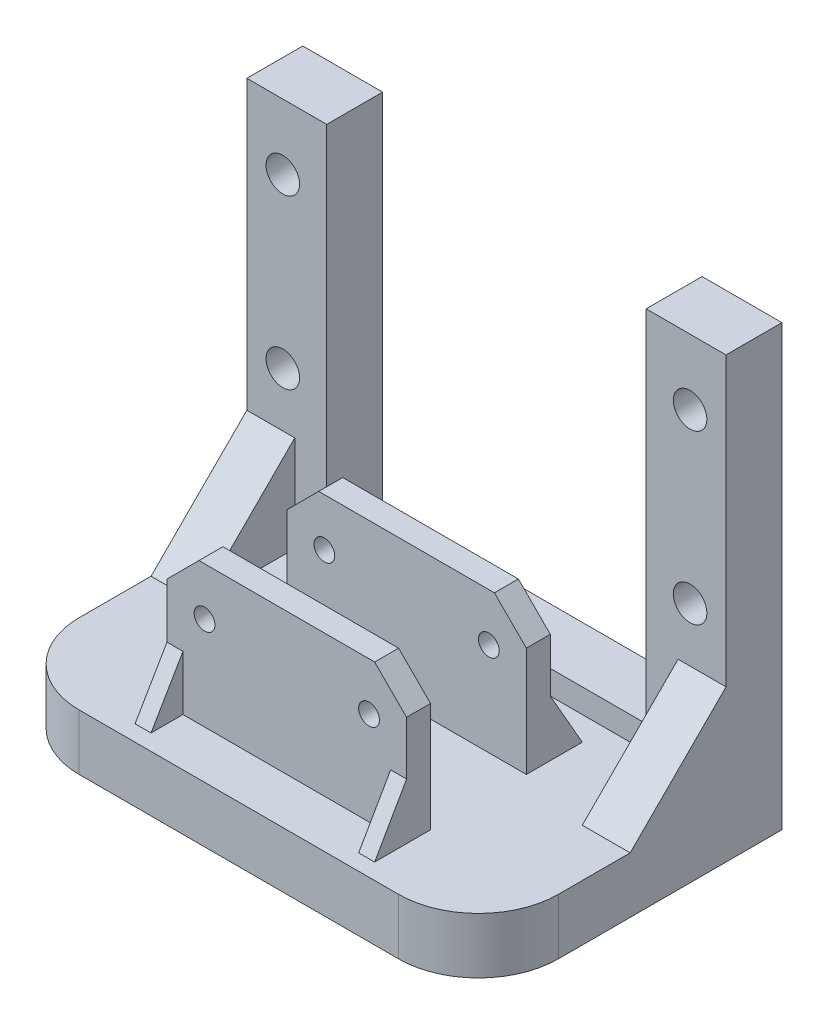
SolidWorks part; units mm, degrees
material "ABS"
ref_plane "前视基准面" through (0, 0, 0) normal (0, 0, 1) x (1, 0, 0)
ref_plane "上视基准面" through (0, 0, 0) normal (0, 1, 0) x (1, 0, 0)
ref_plane "右视基准面" through (0, 0, 0) normal (1, 0, 0) x (0, 0, -1)
other "Configuration Table"
sketch "草图2" plane through (0, 0, 0) normal (0, 0, 1) x (1, 0, 0)
  line L0 (0, 17.5458) -> (0, -16.2036) construction
  line L1 (-11, 11) -> (11, 11)
  line L2 (-15, 7) -> (-15, -11)
  line L3 (-15, -11) -> (15, -11)
  line L5 (-17.0124, 0) -> (19.7175, 0) construction
  line L7 (-15, 7) -> (-11, 11)
  line L8 (15, 7) -> (11, 11)
  line L9 (15, 7) -> (15, -11)
  circle A0 centre (-10.3, 5) radius 1.3
  circle A1 centre (10.3, 5) radius 1.3
  point P0 (0, 0)
  point P4 (0, -11)
  point P15 (0, 11)
  dimension "D4" = 2.6
  dimension "D1" = 18
  dimension "D2" = 15
  dimension "D3" = 16
  dimension "D5" = 11
  dimension "D6" = 22
  dimension "D7" = 10.3
extrude "凸台-拉伸1" add sketch "草图2" along normal mid plane 18
sketch "草图3" plane through (0, 0, 0) normal (0, 0, 1) x (1, 0, 0)
  line L0 (-15, 7) -> (-15, -11) construction
  line L1 (-15, -6.7) -> (15, -6.7)
  line L2 (-15, -6.7) -> (-15, 14.1356)
  line L3 (-15, 14.1356) -> (15, 14.1356)
  line L4 (15, -6.7) -> (15, 14.1356)
  line L5 (15, -11) -> (15, 7) construction
  line L6 (-15, -11) -> (15, -11) construction
  dimension "D1" = 4.3
extrude "切除-拉伸1" cut sketch "草图3" against normal mid plane 12
sketch "草图6" plane through (0, 0, 0) normal (0, 1, 0) x (1, 0, 0)
  line L0 (0, 27.975) -> (0, -21.7187) construction
  line L7 (31, 23) -> (-31, 23) construction
  line L8 (-20, -15) -> (20, -15)
  line L9 (-30, -5) -> (-30, 23)
  line L10 (-30, 23) -> (30, 23)
  line L11 (30, -5) -> (30, 23)
  line L12 (-30, -15) -> (30, 23) construction
  line L13 (-30, 23) -> (30, -15) construction
  arc A4 (-20, -15) -> (-30, -5) centre (-20, -5) cw
  arc A5 (30, -5) -> (20, -15) centre (20, -5) cw
  point P0 (0, 0)
  point P8 (0, 4)
  dimension "D3" = 38
  dimension "D4" = 60
  dimension "D1" = 10
  dimension "D2" = 10
extrude "凸台-拉伸2" add sketch "草图6" against normal blind 7 from surface at -6.7 starting at face at (0, -6.7, 0)
sketch "草图7" plane through (15, 0, 0) normal (1, 0, 0) x (0, 0, -1)
  line L0 (0, 12.9393) -> (0, -16.8041) construction
  line L1 (-9, 0.3) -> (-13, -6.7)
  line L2 (-9, -6.7) -> (-9, 7) construction
  line L4 (-13, -6.7) -> (-9, -6.7)
  line L5 (-9, -6.7) -> (-9, 0.3)
  line L6 (9, -6.7) -> (9, 0.3)
  line L7 (13, -6.7) -> (9, -6.7)
  line L8 (9, 0.3) -> (13, -6.7)
  dimension "D1" = 7
  dimension "D2" = 4
extrude "凸台-拉伸3" add sketch "草图7" against normal blind 2
sketch "草图10" plane through (-15, 0, 0) normal (-1, 0, 0) x (0, 0, 1)
  line L0 (0, 11.4837) -> (0, -16.1999) construction
  line L1 (-9, 0.15) -> (-13, -6.7)
  line L2 (-9, 7) -> (-9, -6.7) construction
  line L3 (-13, -6.7) -> (-9, -6.7)
  line L4 (-9, -6.7) -> (-9, 0.15)
  line L5 (9, -6.7) -> (9, 0.15)
  line L6 (13, -6.7) -> (9, -6.7)
  line L7 (9, 0.15) -> (13, -6.7)
extrude "凸台-拉伸4" add sketch "草图10" against normal blind 2
sketch "草图11" plane through (0, 0, -23) normal (0, 0, 1) x (1, 0, 0)
  line L1 (-30, -11.7) -> (30, -11.7)
  line L2 (-30, -11.7) -> (-30, 41.3)
  line L3 (-30, 41.3) -> (-20, 41.3)
  line L4 (30, -11.7) -> (30, 41.3)
  line L5 (0, -6.7) -> (0, 40.2901) construction
  line L6 (20, 41.3) -> (30, 41.3)
  line L7 (20, -3.7) -> (-20, -3.7)
  line L8 (20, -3.7) -> (20, 41.3)
  line L10 (-20, -3.7) -> (-20, 41.3)
  line L11 (20, -3.7) -> (-20, 41.3) construction
  line L12 (20, 41.3) -> (-20, -3.7) construction
  line L13 (-31, -13.7) -> (31, -13.7) construction
  line L14 (20, -6.7) -> (-20, -6.7) construction
  line L15 (0, 40.2901) -> (0, -6.7) construction
  circle A0 centre (-25.5, 33.1) radius 2.1
  circle A1 centre (-25.5, 12.1) radius 2.1
  circle A2 centre (25.5, 12.1) radius 2.1
  circle A3 centre (25.5, 33.1) radius 2.1
  point P9 (0, 18.8)
  dimension "D6" = 4.2
  dimension "D7" = 4.2
  dimension "D1" = 45
  dimension "D2" = 53
  dimension "D3" = 40
  dimension "D4" = 2
  dimension "D5" = 60
extrude "凸台-拉伸5" add sketch "草图11" along normal blind 7
sketch "草图12" plane through (-30, 0, 0) normal (-1, 0, 0) x (0, 0, 1)
  line L0 (-4, -6.7) -> (-16, 5.3)
  line L1 (5, -6.7) -> (-16, -6.7) construction
  line L2 (-16, 41.3) -> (-16, -6.7) construction
  line L3 (-16, 5.3) -> (-16, -6.7)
  line L4 (-16, -6.7) -> (-4, -6.7)
  dimension "D1" = 12
  dimension "D2" = 12
extrude "凸台-拉伸6" add sketch "草图12" against normal blind 6
sketch "草图13" plane through (30, 0, 0) normal (1, 0, 0) x (0, 0, -1)
  line L0 (16, -6.7) -> (16, 5.3)
  line L1 (16, 5.3) -> (4, -6.7)
  line L2 (4, -6.7) -> (16, -6.7)
extrude "凸台-拉伸7" add sketch "草图13" against normal blind 6
